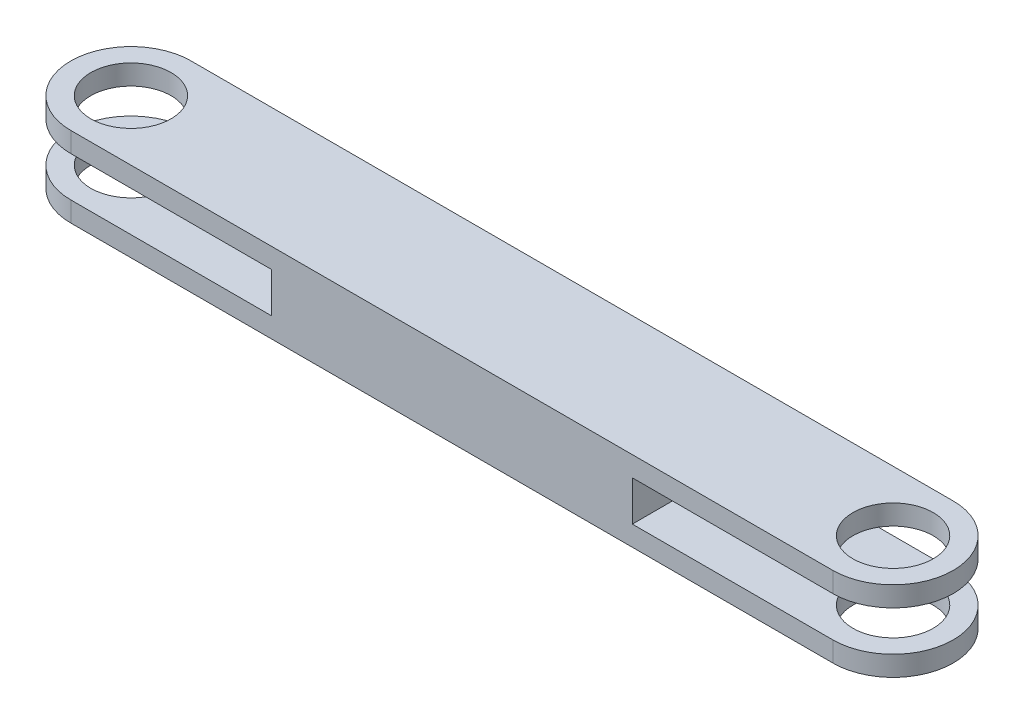
SolidWorks part; units mm, degrees
ref_plane "前基準面" through (0, 0, 0) normal (0, 0, 1) x (1, 0, 0)
ref_plane "上基準面" through (0, 0, 0) normal (0, 1, 0) x (1, 0, 0)
ref_plane "右基準面" through (0, 0, 0) normal (1, 0, 0) x (0, 0, -1)
sketch "草圖1" plane through (0, 0, 0) normal (0, 1, 0) x (1, 0, 0)
  line L1 (-95, 15) -> (95, 15)
  line L2 (-95, 15) -> (-95, -15)
  line L3 (-95, -15) -> (95, -15)
  line L4 (95, 15) -> (95, -15)
  line L5 (-95, 15) -> (95, -15) construction
  line L6 (-95, -15) -> (95, 15) construction
  circle A0 centre (-95, 0) radius 10
  circle A1 centre (-95, 0) radius 15
  circle A2 centre (95, 0) radius 15
  circle A3 centre (95, 0) radius 10
  point P0 (0, 0)
  dimension "D2" = 20
  dimension "D3" = 30
  dimension "D4" = 20
  dimension "D1" = 190
extrude "填料-伸長1" add sketch "草圖1" along normal mid plane 20 contours A2 L1 A1 L3 | L2 A1 A0 | L2 A1 A0 | A3 L4 A2 | A3 L4 A2
sketch "草圖2" plane through (0, 0, 0) normal (0, 1, 0) x (1, 0, 0)
  line L0 (-45, 15) -> (-45, -15)
  line L2 (-95, -15) -> (95, -15)
  line L3 (95, 15) -> (-95, 15)
  line L4 (-95, -15) -> (-45, -15)
  line L5 (-45, 15) -> (-95, 15)
  arc A2 (-95, 15) -> (-95, -15) centre (-95, 0) ccw
  arc A3 (95, -15) -> (95, 15) centre (95, 0) ccw
  arc A4 (-95, 15) -> (-95, -15) centre (-95, 0) ccw
  dimension "D2" = 50
  dimension "D1" = 0
extrude "除料-伸長1" cut sketch "草圖2" against normal mid plane 10
mirror "鏡射1" about plane through (0, 0, 0) normal (1, 0, 0) of "除料-伸長1"
